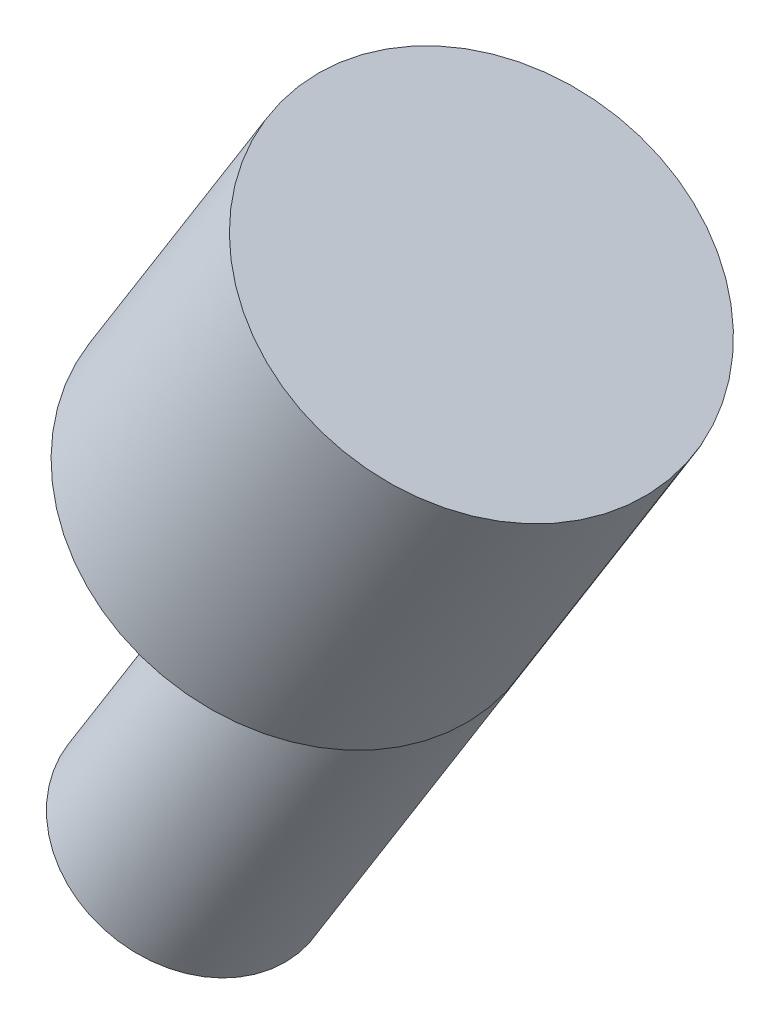
SolidWorks part; units mm, degrees
ref_plane "Plan de face" through (0, 0, 0) normal (0, 0, 1) x (1, 0, 0)
ref_plane "Plan de dessus" through (0, 0, 0) normal (0, 1, 0) x (1, 0, 0)
ref_plane "Plan de droite" through (0, 0, 0) normal (1, 0, 0) x (0, 0, -1)
sketch "Esquisse1" plane through (0.8076, 1.2922, 0) normal (-0.53, -0.848, 0) x (0.848, -0.53, 0)
  circle A0 centre (-28.8193, -165) radius 2.3
  circle A2 centre (-28.8193, -165) radius 2.3 construction
extrude "Boss.-Extru.1" add sketch "Esquisse1" against normal up to surface (15 mm away)
sketch "Esquisse2" plane through (8.7576, 14.0122, 0) normal (0.53, 0.848, 0) x (0.848, -0.53, 0)
  circle A0 centre (-28.8193, 159.375) radius 4
  circle A2 centre (-28.8193, 159.375) radius 4 construction
extrude "Boss.-Extru.2" add sketch "Esquisse2" along normal blind 7
